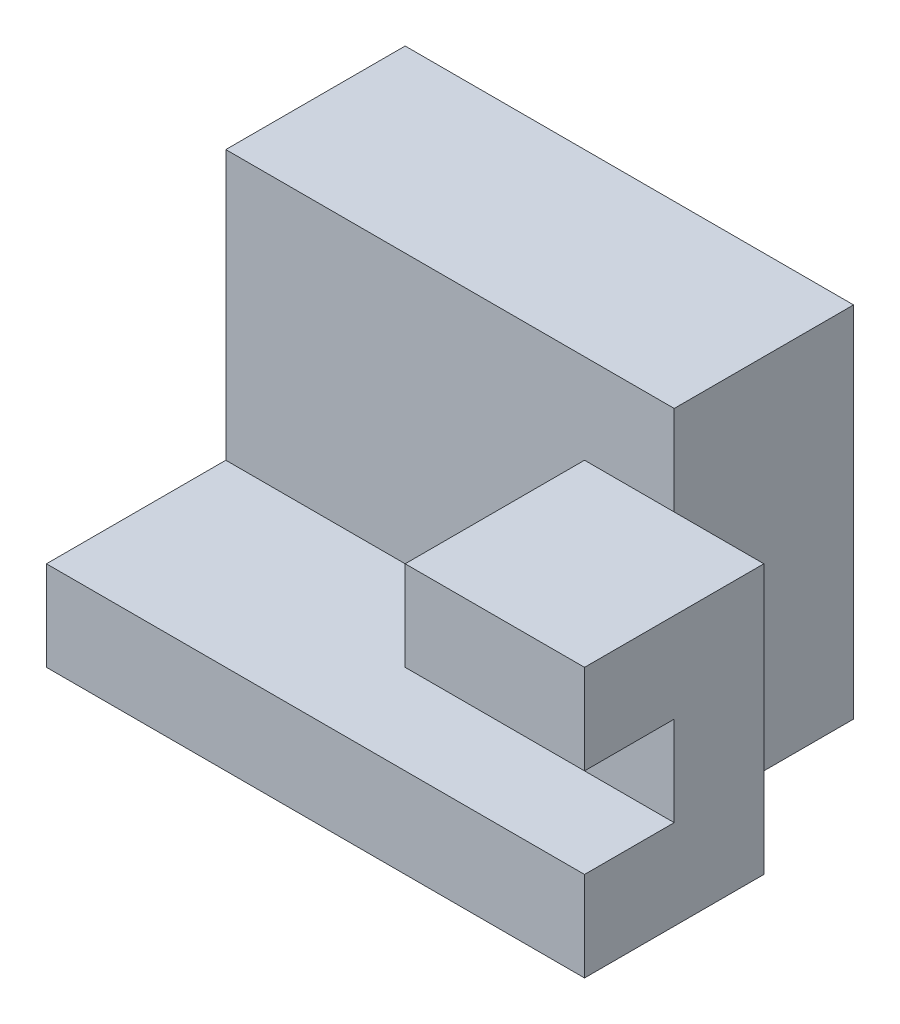
SolidWorks part; units mm, degrees
ref_plane "Front Plane" through (0, 0, 0) normal (0, 0, 1) x (1, 0, 0)
ref_plane "Top Plane" through (0, 0, 0) normal (0, 1, 0) x (1, 0, 0)
ref_plane "Right Plane" through (0, 0, 0) normal (1, 0, 0) x (0, 0, -1)
sketch "Sketch1" plane through (0, 0, 0) normal (0, 1, 0) x (1, 0, 0)
  line L1 (-25, 10) -> (25, 10)
  line L2 (-25, 10) -> (-25, -10)
  line L3 (-25, -10) -> (25, -10)
  line L4 (25, 10) -> (25, -10)
  line L5 (-25, 10) -> (25, -10) construction
  line L6 (-25, -10) -> (25, 10) construction
  point P0 (0, 0)
  dimension "D1" = 20
  dimension "D2" = 50
extrude "Boss-Extrude1" add sketch "Sketch1" against normal blind 40
sketch "Sketch2" plane through (-25, 0, 0) normal (-1, 0, 0) x (0, 0, 1)
  line L0 (10, -30) -> (10, -40)
  line L1 (10, -40) -> (10, 0) construction
  line L2 (10, -40) -> (30, -40)
  line L3 (30, -40) -> (30, -30)
  line L4 (30, -30) -> (10, -30)
  dimension "D1" = 20
  dimension "D2" = 10
extrude "Boss-Extrude2" add sketch "Sketch2" against normal blind 40
sketch "Sketch3" plane through (15, 0, 0) normal (1, 0, 0) x (0, 0, -1)
  line L1 (-30, -40) -> (-10, -40)
  line L2 (-10, -40) -> (-10, -10)
  line L3 (-10, -40) -> (-10, 0) construction
  line L4 (-10, -10) -> (-30, -10)
  line L5 (-30, -10) -> (-30, -20)
  line L6 (-30, -20) -> (-20, -20)
  line L7 (-20, -20) -> (-20, -30)
  line L8 (-20, -30) -> (-30, -30)
  line L10 (-30, -30) -> (-30, -40)
  dimension "D1" = 30
  dimension "D2" = 10
  dimension "D3" = 10
  dimension "D4" = 10
  dimension "D5" = 10
extrude "Boss-Extrude3" add sketch "Sketch3" along normal blind 20
